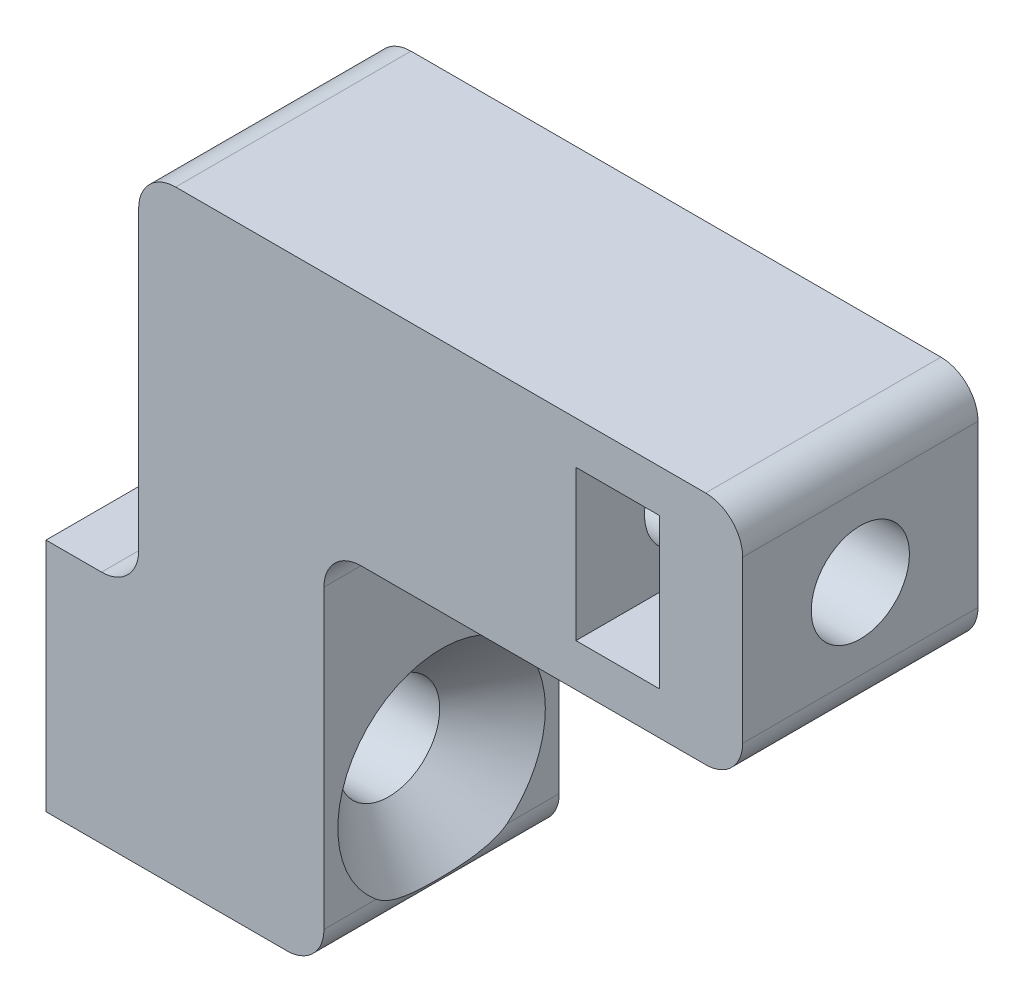
SolidWorks part; units mm, degrees
ref_plane "Front Plane" through (0, 0, 0) normal (0, 0, 1) x (1, 0, 0)
ref_plane "Top Plane" through (0, 0, 0) normal (0, 1, 0) x (1, 0, 0)
ref_plane "Right Plane" through (0, 0, 0) normal (1, 0, 0) x (0, 0, -1)
sketch "Sketch1" plane through (0, 0, 0) normal (0, 0, 1) x (1, 0, 0)
  line L0 (25.1, 0) -> (25.1, 2.5) construction
  line L1 (0, -20) -> (39.4083, -20) construction
  line L2 (0, -26.35) -> (0, -13.65)
  line L3 (0, -13.65) -> (5, -13.65)
  line L4 (5, -13.65) -> (5, 6.35)
  line L5 (5, 6.35) -> (37.6, 6.35)
  line L6 (0, -26.35) -> (15, -26.35)
  line L7 (15, -26.35) -> (15, -6.35)
  line L8 (15, -6.35) -> (37.6, -6.35)
  line L9 (37.6, -6.35) -> (37.6, 6.35)
  line L10 (0, 0) -> (20, 0) construction
  line L11 (20, 0) -> (58.1, 0) construction
  line L12 (45.1, 0) -> (45.1, 2.5) construction
  line L13 (45.1, 2.5) -> (25.1, 2.5) construction
  line L14 (28.6, 0) -> (28.6, 4.6188) construction
  line L15 (28.6, 4.6188) -> (32.6, 4.6188) construction
  line L16 (32.6, 4.6188) -> (32.6, 0) construction
  line L17 (62.1, 0) -> (58.1, 0) construction
  line L24 (62.1, 0) -> (62.1, 4.6188) construction
  line L25 (60.1, 3.4641) -> (58.1, 2.3094) construction
  line L26 (58.1, 2.3094) -> (58.1, 0) construction
  line L27 (60.1, 3.4641) -> (62.1, 4.6188) construction
  line L28 (28.6, 4) -> (32.6, 4) construction
  line L29 (15, -20) -> (15, -17.5) construction
  line L30 (15, -17.5) -> (-5, -17.5) construction
  line L31 (-5, -17.5) -> (-5, -20) construction
  line L32 (-5, -20) -> (15, -20) construction
  point P23 (37.6, 0)
  dimension "D1" = 20
  dimension "D2" = 5
  dimension "D3" = 12.7
  dimension "D4" = 5
  dimension "D5" = 20
  dimension "D6" = 38.1
  dimension "D7" = 33
  dimension "D8" = 20
  dimension "D9" = 2.5
  dimension "D10" = 4
  dimension "D11" = 5
  dimension "D12" = 4
  dimension "D13" = 120
  dimension "D14" = 12.7
  dimension "D15" = 7.5
  dimension "D16" = 1.7312
  dimension "D17" = 4
  dimension "D18" = 2.35
  dimension "D19" = 15
  dimension "D20" = 20
  dimension "D21" = 2.5
  dimension "D22" = 10
extrude "Boss-Extrude2" add sketch "Sketch1" along normal blind 12.7
fillet "Fillet1" radius 2 6 edges at (5, -13.65, 6.35) (5, 6.35, 6.35) (15, -26.35, 6.35) (15, -6.35, 6.35) (37.6, 6.35, 6.35) (37.6, -6.35, 6.35)
sketch "Sketch2" plane through (15, 0, 0) normal (1, 0, 0) x (0, 0, -1)
  line L0 (-12.7, -13.65) -> (0, -13.65) construction
  line L1 (-12.7, -13.65) -> (-12.7, -26.35) construction
  line L2 (-12.7, -13.65) -> (0, -13.65) construction
  line L3 (-12.7, -13.65) -> (-12.7, -26.35) construction
  line L4 (-6.35, -13.65) -> (-6.35, -20) construction
  line L5 (-6.35, -20) -> (-12.7, -20) construction
hole_wizard "CSK for M5 SFHCS1" positions "Sketch3" profile "Sketch4" countersink size "M5" standard "ANSI Metric" end condition through all
sketch "Sketch3" plane through (15, 0, 0) normal (1, 0, 0) x (0, 0, -1)
  point P0 (-6.35, -20)
sketch "Sketch4" plane through (15, -20, 6.35) normal (0, 1, 0) x (0, 0, -1)
  line L0 (0, 0) -> (0, 15)
  line L1 (0, 15) -> (2.75, 15)
  line L2 (2.75, 15) -> (2.75, 2.85)
  line L3 (2.75, 2.85) -> (5.6, 0)
  line L5 (5.6, 0) -> (0, 0)
  line L6 (-2.75, 2.85) -> (-5.6, 0) construction
  line L11 (0, -6.35) -> (0, 107.95) construction
  dimension "Thru Hole Dia." = 5.5
  dimension "Thru Hole Depth" = 15
  dimension "Near C'Sink Dia." = 11.2
  dimension "Near C'Sink Angle" = 90
sketch "Sketch5" plane through (37.6, 0, 0) normal (1, 0, 0) x (0, 0, -1)
  line L0 (-6.35, 6.35) -> (-6.35, 0) construction
  line L1 (-12.7, 6.35) -> (0, 6.35) construction
  line L2 (-6.35, 0) -> (-12.7, 0) construction
  line L3 (-12.7, -4.35) -> (-12.7, 4.35) construction
hole_wizard "M5 Clearance Hole1" positions "Sketch6" profile "Sketch7" hole size "M5" standard "ANSI Metric" end condition through all
sketch "Sketch6" plane through (37.6, 0, 0) normal (1, 0, 0) x (0, 0, -1)
  point P0 (-6.35, 0)
sketch "Sketch7" plane through (37.6, 0, 6.35) normal (0, 1, 0) x (0, 0, -1)
  line L0 (0, 0) -> (0, 37.6)
  line L1 (0, 37.6) -> (2.65, 37.6)
  line L2 (2.65, 37.6) -> (2.65, 0)
  line L5 (2.65, 0) -> (0, 0)
  line L11 (0, -6.35) -> (0, 107.95) construction
  dimension "Thru Hole Dia." = 5.3
  dimension "Thru Hole Depth" = 37.6
ref_plane "Plane1" through (28.6, 0, 0) normal (1, 0, 0) x (0, 0, -1)
sketch "Sketch8" plane through (28.6, 0, 0) normal (1, 0, 0) x (0, 0, -1)
  line L0 (-12.7, 4.05) -> (-6.35, 4.05)
  line L1 (-6.35, 4.05) -> (-4.0117, 4.05)
  line L2 (-4.0117, 4.05) -> (-1.6735, 0)
  line L3 (-1.6735, 0) -> (-4.0117, -4.05)
  line L4 (-4.0117, -4.05) -> (-6.35, -4.05)
  line L5 (-6.35, -4.05) -> (-12.7, -4.05)
  line L6 (-12.7, -4.05) -> (-12.7, 4.05)
  line L7 (-12.7, -4.35) -> (-12.7, 4.35) construction
  circle A0 centre (-6.35, 0) radius 4.05 construction
  dimension "D3" = 8.1
  dimension "D1" = 120
  dimension "D2" = 120
extrude "Cut-Extrude1" cut sketch "Sketch8" along normal blind 4.5
